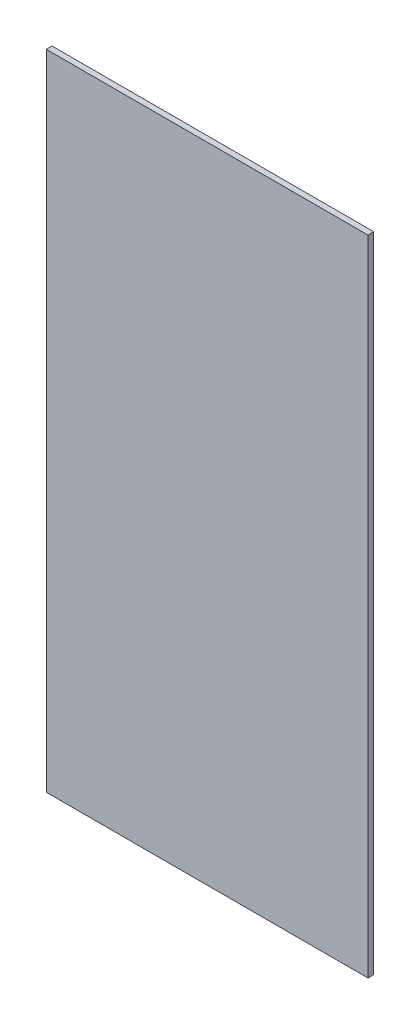
SolidWorks part; units mm, degrees
ref_plane "Front Plane" through (0, 0, 0) normal (0, 0, 1) x (1, 0, 0)
ref_plane "Top Plane" through (0, 0, 0) normal (0, 1, 0) x (1, 0, 0)
ref_plane "Right Plane" through (0, 0, 0) normal (1, 0, 0) x (0, 0, -1)
sketch "Sketch1" plane through (0, 0, 0) normal (0, 0, 1) x (1, 0, 0)
  line L1 (88.9, 177.8) -> (-88.9, 177.8)
  line L2 (88.9, 177.8) -> (88.9, -177.8)
  line L3 (88.9, -177.8) -> (-88.9, -177.8)
  line L4 (-88.9, 177.8) -> (-88.9, -177.8)
  line L5 (88.9, 177.8) -> (-88.9, -177.8) construction
  line L6 (88.9, -177.8) -> (-88.9, 177.8) construction
  point P0 (0, 0)
  dimension "D1" = 355.6
  dimension "D2" = 177.8
extrude "Boss-Extrude1" add sketch "Sketch1" along normal blind 3.175
